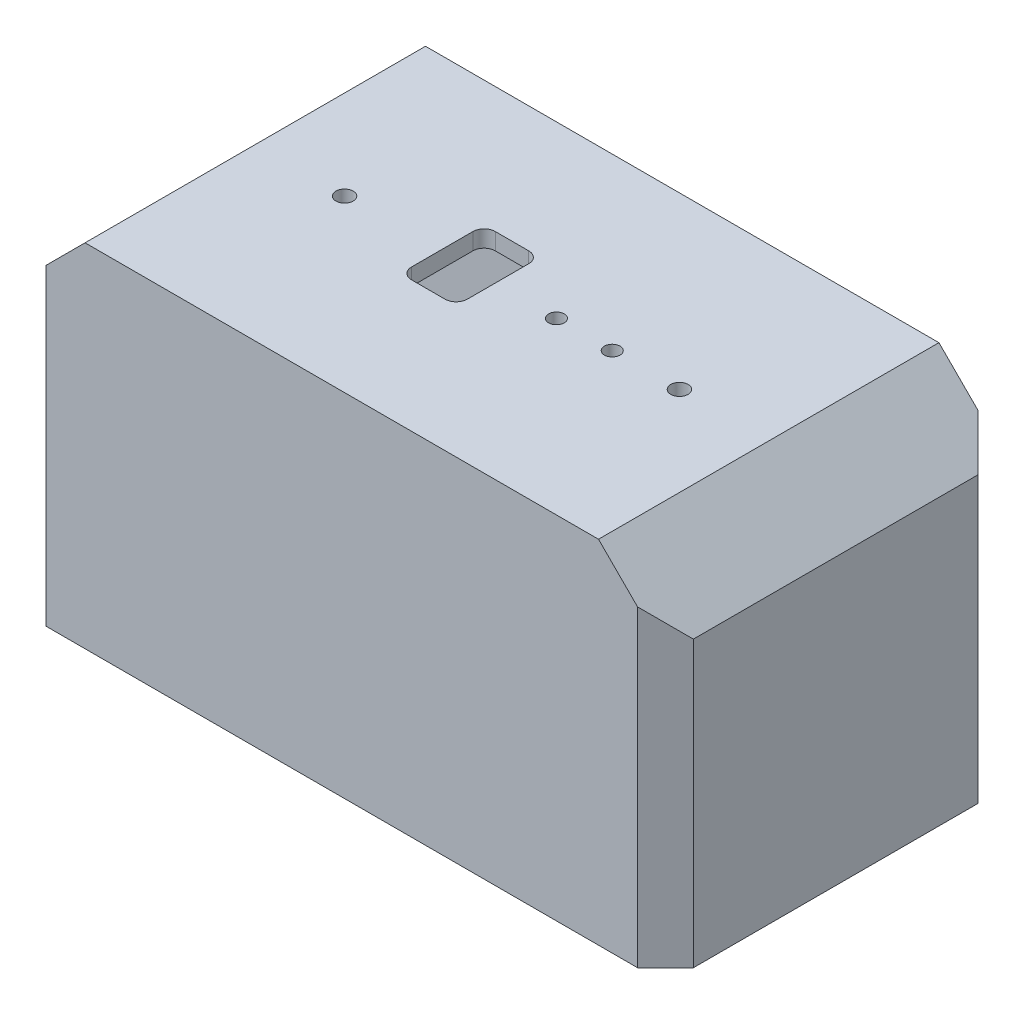
SolidWorks part; units mm, degrees
ref_plane "Front Plane" through (0, 0, 0) normal (0, 0, 1) x (1, 0, 0)
ref_plane "Top Plane" through (0, 0, 0) normal (0, 1, 0) x (1, 0, 0)
ref_plane "Right Plane" through (0, 0, 0) normal (1, 0, 0) x (0, 0, -1)
sketch "Sketch1" plane through (0, 0, 0) normal (0, 1, 0) x (1, 0, 0)
  line L1 (-55, 27.5) -> (55, 27.5)
  line L2 (-55, 27.5) -> (-55, -27.5)
  line L3 (-55, -27.5) -> (55, -27.5)
  line L4 (55, 27.5) -> (55, -27.5)
  line L5 (-55, 27.5) -> (55, -27.5) construction
  line L6 (-55, -27.5) -> (55, 27.5) construction
  line L7 (-58, 30.5) -> (58, 30.5)
  line L8 (-58, 30.5) -> (-58, -30.5)
  line L9 (-58, -30.5) -> (58, -30.5)
  line L10 (58, 30.5) -> (58, -30.5)
  line L11 (-58, 30.5) -> (58, -30.5) construction
  line L12 (-58, -30.5) -> (58, 30.5) construction
  point P0 (0, 0)
  point P6 (0, 0)
  dimension "D1" = 110
  dimension "D2" = 55
  dimension "D3" = 3
  dimension "D4" = 3
extrude "Boss-Extrude1" add sketch "Sketch1" along normal blind 60
sketch "Sketch2" plane through (0, 60, 0) normal (0, 1, 0) x (1, 0, 0)
  line L1 (-58, 30.5) -> (58, 30.5)
  line L2 (-58, 30.5) -> (-58, -30.5)
  line L3 (-58, -30.5) -> (58, -30.5)
  line L4 (58, 30.5) -> (58, -30.5)
  line L5 (-58, 30.5) -> (58, -30.5) construction
  line L6 (-58, -30.5) -> (58, 30.5) construction
  point P0 (0, 0)
extrude "Boss-Extrude2" add sketch "Sketch2" along normal blind 3
chamfer "Chamfer1" distance 5 angle 45 4 edges at (-58, 31.5, -30.5) (58, 31.5, -30.5) (58, 31.5, 30.5) (-58, 31.5, 30.5)
chamfer "Chamfer2" distance 6 angle 45 4 edges at (55, 30, -27.5) (-55, 30, -27.5) (55, 30, 27.5) (-55, 30, 27.5)
sketch "Sketch3" plane through (0, 63, 0) normal (0, 1, 0) x (1, 0, 0)
  line L0 (58, -25.5) -> (58, 25.5) construction
  circle A0 centre (30, 0) radius 1.55
  circle A1 centre (-30, 0) radius 1.55
  dimension "D1" = 3.1
  dimension "D2" = 3.1
  dimension "D3" = 60
  dimension "D4" = 28
extrude "Cut-Extrude1" cut sketch "Sketch3" against normal blind 3
sketch "Sketch4" plane through (0, 63, 0) normal (0, 1, 0) x (1, 0, 0)
  line L0 (53, 30.5) -> (-53, 30.5) construction
  line L1 (-13, 8) -> (-3, 8)
  line L2 (-13, 8) -> (-13, -7)
  line L3 (-13, -7) -> (-3, -7)
  line L4 (-3, 8) -> (-3, -7)
  line L5 (-13, 8) -> (-3, -7) construction
  line L6 (-13, -7) -> (-3, 8) construction
  circle A0 centre (-30, 0) radius 1.55 construction
  point P0 (-8, 0.5)
  dimension "D1" = 15
  dimension "D2" = 10
  dimension "D3" = 17
  dimension "D4" = 22.5
extrude "Cut-Extrude2" cut sketch "Sketch4" against normal blind 3
sketch "Sketch5" plane through (0, 0, 0) normal (0, -1, 0) x (1, 0, 0)
  line L0 (58, 25.5) -> (58, -25.5) construction
  line L1 (53, -30.5) -> (-53, -30.5) construction
  line L2 (-58, -25.5) -> (-58, 25.5) construction
  line L3 (-53, 30.5) -> (53, 30.5) construction
  circle A0 centre (53.7, -26.2) radius 1.4
  circle A1 centre (-53.7, -26.2) radius 1.4
  circle A2 centre (-53.7, 26.2) radius 1.4
  circle A3 centre (53.7, 26.2) radius 1.4
  dimension "D1" = 2.8
  dimension "D2" = 4.3
  dimension "D3" = 4.3
  dimension "D4" = 2.8
  dimension "D5" = 4.3
  dimension "D6" = 4.3
  dimension "D7" = 2.8
  dimension "D8" = 4.3
  dimension "D9" = 4.3
  dimension "D10" = 2.8
  dimension "D11" = 4.3
  dimension "D12" = 4.3
extrude "Cut-Extrude3" cut sketch "Sketch5" against normal blind 20
fillet "Fillet1" radius 2 4 edges at (-3, 61.5, 7) (-13, 61.5, 7) (-3, 61.5, -8) (-13, 61.5, -8)
chamfer "Chamfer3" distance 12 angle 45 2 edges at (58, 63, 0) (-58, 63, 0)
chamfer "Chamfer4" distance 10 angle 45 2 edges at (55, 60, 0) (-55, 60, 0)
sketch "Sketch6" plane through (0, 0, -30.5) normal (0, 0, -1) x (-1, 0, 0)
  line L0 (-53, 0) -> (53, 0) construction
  line L1 (-29.25, 0) -> (29.25, 0)
  line L2 (-29.25, 0) -> (-29.25, 9.5)
  line L3 (-29.25, 9.5) -> (29.25, 9.5)
  line L4 (29.25, 0) -> (29.25, 9.5)
  line L5 (53, 0) -> (53, 56) construction
  dimension "D1" = 58.5
  dimension "D2" = 9.5
  dimension "D3" = 23.75
extrude "Cut-Extrude4" cut sketch "Sketch6" against normal blind 10
sketch "Sketch7" plane through (0, 63, 0) normal (0, 1, 0) x (1, 0, 0)
  circle A0 centre (7.9598, 0) radius 1.4
  circle A1 centre (17.9598, 0) radius 1.4
  dimension "D1" = 2.8
  dimension "D2" = 2.8
  dimension "D3" = 10
extrude "Cut-Extrude5" cut sketch "Sketch7" against normal blind 10
sketch "Sketch8" plane through (0, 60, 0) normal (0, -1, 0) x (1, 0, 0)
  circle A0 centre (7.9598, 0) radius 3
  circle A1 centre (17.9598, 0) radius 3
  circle A2 centre (17.9598, 0) radius 1.4
  circle A3 centre (7.9598, 0) radius 1.4
  dimension "D1" = 6
  dimension "D2" = 6
extrude "Boss-Extrude3" add sketch "Sketch8" along normal blind 4
